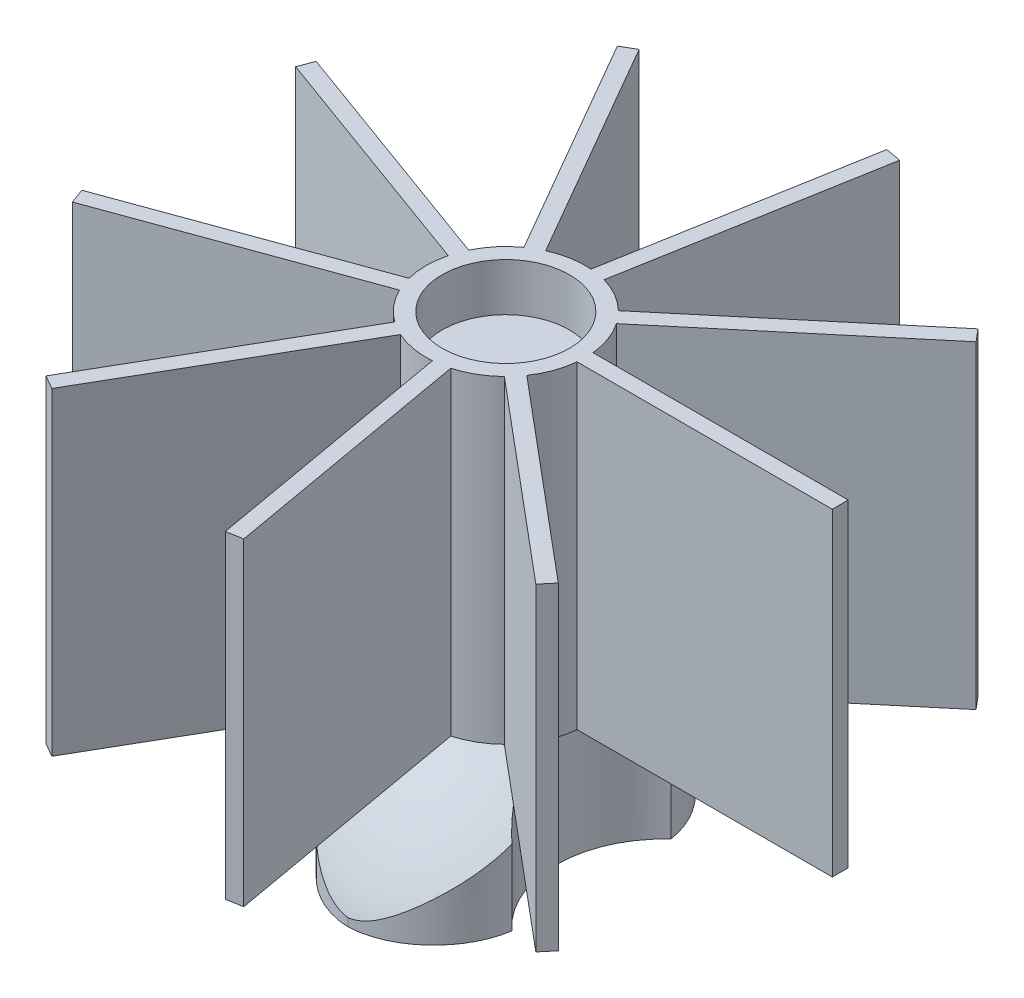
SolidWorks part; units mm, degrees
ref_plane "Front Plane" through (0, 0, 0) normal (0, 0, 1) x (1, 0, 0)
ref_plane "Top Plane" through (0, 0, 0) normal (0, 1, 0) x (1, 0, 0)
ref_plane "Right Plane" through (0, 0, 0) normal (1, 0, 0) x (0, 0, -1)
sketch "Sketch1" plane through (0, 0, 0) normal (0, 1, 0) x (1, 0, 0)
  circle A0 centre (0, 0) radius 5
  circle A1 centre (0, 0) radius 3
  dimension "D1" = 6
  dimension "D2" = 10
extrude "Boss-Extrude2" add sketch "Sketch1" along normal mid plane 35
sketch "Sketch4" plane through (0, 17.5, 0) normal (0, 1, 0) x (1, 0, 0)
  line L0 (3, 0) -> (21, 0)
  circle A0 centre (0, 0) radius 3 construction
  dimension "D1" = 18
extrude "Extrude-Thin1" add sketch "Sketch4" against normal blind 35 thin thin type mid plane wall 1
pattern_circular "CirPattern1" count 9 over 360 about axis through (0, 0, 0) along (0, 1, 0) of "Extrude-Thin1"
ref_plane "Plane1" through (0, -17.5, 0) normal (0, -1, 0) x (-1, 0, 0)
sketch "Sketch5" plane through (0, -17.5, 0) normal (0, -1, 0) x (-1, 0, 0)
  circle A0 centre (0, 0) radius 3
extrude "Boss-Extrude3" add sketch "Sketch5" against normal blind 15
sketch "Sketch6" plane through (0, -17.5, 0) normal (0, -1, 0) x (-1, 0, 0)
  circle A0 centre (0, 0) radius 3.5
  circle A1 centre (0, 0) radius 5
  circle A2 centre (0, 0) radius 1.5
  dimension "D1" = 1.5
  dimension "D2" = 10
  dimension "D3" = 2
extrude "Cut-Extrude1" cut sketch "Sketch6" against normal blind 6 contours A0 A2
sketch "Sketch15" plane through (0, -17.5, 0) normal (0, -1, 0) x (1, 0, 0)
  circle A0 centre (0, 0) radius 1.5
extrude "Cut-Extrude2" cut sketch "Sketch15" against normal blind 2
sketch "Sketch17" plane through (0, -17.5, 0) normal (0, -1, 0) x (1, 0, 0)
  line L0 (21, -0.5) -> (21, 0.5) construction
  circle A0 centre (18.5, 0) radius 2.5
  dimension "D1" = 5
  dimension "D2" = 2.5
extrude "Boss-Extrude4" add sketch "Sketch17" against normal blind 3
sketch "Sketch18" plane through (0, -17.5, 0) normal (0, -1, 0) x (1, 0, 0)
  circle A0 centre (18.5, 0) radius 2
  dimension "D1" = 4
extrude "Cut-Extrude3" cut sketch "Sketch18" against normal blind 2
sketch "Sketch19" plane through (0, 17.5, 0) normal (0, 1, 0) x (1, 0, 0)
  circle A0 centre (0, 0) radius 4
  circle A1 centre (0, 0) radius 3 construction
  dimension "D1" = 1
extrude "Cut-Extrude4" cut sketch "Sketch19" against normal up to surface (20 mm away) up to face at (0, -2.5, -3)
sketch "Sketch20" plane through (0, -17.5, 0) normal (0, -1, 0) x (-1, 0, 0)
  line L1 (22.8386, 22.8623) -> (-22.8386, 22.8623)
  line L2 (22.8386, 22.8623) -> (22.8386, -22.8623)
  line L3 (22.8386, -22.8623) -> (-22.8386, -22.8623)
  line L4 (-22.8386, 22.8623) -> (-22.8386, -22.8623)
  line L5 (22.8386, 22.8623) -> (-22.8386, -22.8623) construction
  line L6 (22.8386, -22.8623) -> (-22.8386, 22.8623) construction
  point P0 (0, 0)
extrude "Cut-Extrude5" cut sketch "Sketch20" against normal blind 8
sketch "Sketch21" plane through (0, -9.5, 0) normal (0, -1, 0) x (1, 0, 0)
  circle A0 centre (0, 0) radius 3
  dimension "D1" = 6
extrude "Boss-Extrude5" add sketch "Sketch21" along normal blind 1
sketch "Sketch22" plane through (0, 0, 0) normal (0, 0, 1) x (1, 0, 0)
  line L0 (0, 0) -> (0, -37.0893) construction
sketch "Sketch23" plane through (0, 0, 0) normal (1, 0, 0) x (0, 0, -1)
  line L0 (-8.7928, -17.5) -> (7.1377, -17.5) construction
  line L1 (-13.1155, -9.5) -> (-2.8148, -9.5) construction
  line L2 (-55, -17.5) -> (55, -17.5) construction
  line L3 (-3, -10.5) -> (-2, -10.5)
  line L4 (-3, -10.5) -> (3, -10.5) construction
  line L5 (-9.9121, -17.5) -> (-8.9121, -17.5)
  line L6 (0, -11.1307) -> (0, -16.3839) construction
  line L7 (0, 0) -> (0, -37.0893) construction
  line L8 (-8.9121, -17.5) -> (0, -17.5)
  line L9 (0, -17.5) -> (0, -10.5)
  line L10 (0, -10.5) -> (-2, -10.5)
  arc A0 (-3, -10.5) -> (-9.9121, -17.5) centre (0.7568, -21.1223) ccw
  dimension "D1" = 8
  dimension "D2" = 1
  dimension "D3" = 1
revolve "Revolve1" add sketch "Sketch23" angle 360 about L6
sketch "Sketch24" plane through (0, -17.5, 0) normal (0, -1, 0) x (1, 0, 0)
  circle A2 centre (0, 0) radius 9.9121
  circle A3 centre (0, 0) radius 9.9121
  dimension "D1" = 0
extrude "Boss-Extrude6" add sketch "Sketch24" along normal blind 0.5
sketch "Sketch25" plane through (0, -18, 0) normal (0, -1, 0) x (1, 0, 0)
  line L0 (-1.1163, 9.8491) -> (1.1163, -9.8491) construction
  circle A0 centre (0, 0) radius 9.9121 construction
  circle A1 centre (-0.5667, 5) radius 3.2
  point P6 (0, 0)
  dimension "D1" = 6.4
  dimension "D2" = 5
extrude "Cut-Extrude6" cut sketch "Sketch25" against normal blind 2.1
sketch "Sketch26" plane through (0, -18, 0) normal (0, -1, 0) x (1, 0, 0)
  circle A0 centre (-0.5667, 5) radius 3.2
extrude "Boss-Extrude7" add sketch "Sketch26" against normal blind 0.25
sketch "Sketch27" plane through (0, -18, 0) normal (0, -1, 0) x (1, 0, 0)
  line L0 (0, 9.9121) -> (0, -9.9121) construction
  line L1 (-9.9121, 0) -> (9.9121, 0) construction
  arc A1 (-7.6138, 6.3467) -> (-7.6138, -6.3467) centre (-9.9121, 0) cw
  circle A2 centre (0, 0) radius 9.9121 construction
  arc A3 (7.6138, 6.3467) -> (7.6138, -6.3467) centre (9.9121, 0) ccw
  arc A4 (7.6138, 6.3467) -> (7.6138, -6.3467) centre (0, 0) cw
  arc A5 (-7.6138, 6.3467) -> (-7.6138, -6.3467) centre (0, 0) ccw
  arc A6 (-7.6138, 6.3467) -> (0, 9.9121) centre (0, 0) cw
  arc A7 (7.6138, 6.3467) -> (0, 9.9121) centre (0, 0) ccw
  arc A8 (7.6138, -6.3467) -> (0, -9.9121) centre (0, 0) cw
  arc A9 (-7.6138, -6.3467) -> (0, -9.9121) centre (0, 0) ccw
  spline S0 degree 3 poles (-5.3686, 4.9919) (-4.9981, 7.5397) (-2.6164, 9.8379) (0, 9.9121) knots 0 0 0 0 1 1 1 1
  spline S1 degree 3 poles (5.3686, 4.9919) (4.9981, 7.5397) (2.6164, 9.8379) (0, 9.9121) knots 0 0 0 0 1 1 1 1
  spline S2 degree 3 poles (5.3686, -4.9919) (4.9981, -7.5397) (2.6164, -9.8379) (0, -9.9121) knots 0 0 0 0 1 1 1 1
  spline S3 degree 3 poles (-5.3686, -4.9919) (-4.9981, -7.5397) (-2.6164, -9.8379) (0, -9.9121) knots 0 0 0 0 1 1 1 1
  circle M1 centre (0, 0) radius 9.9121
extrude "Cut-Extrude8" cut sketch "Sketch27" against normal blind 7.5 contours A1 M1 | A3 M1 | S3 A1 M1 | A3 S2 M1 | A1 S0 M1 | S1 A3 M1
sketch "Sketch28" plane through (0, -18, 0) normal (0, -1, 0) x (1, 0, 0)
  circle A0 centre (0, 0) radius 0.5
  dimension "D1" = 1
extrude "Cut-Extrude9" cut sketch "Sketch28" against normal blind 1.5
sketch "Sketch29" plane through (0, 17.5, 0) normal (0, 1, 0) x (1, 0, 0)
  line L108 (3.4896, -3.5809) -> (15.7655, -13.8816)
  line L109 (15.7655, -13.8816) -> (16.4083, -13.1155)
  line L110 (16.4083, -13.1155) -> (4.1324, -2.8148)
  line L111 (4.9749, -0.5) -> (21, -0.5)
  line L112 (21, -0.5) -> (21, 0.5)
  line L113 (21, 0.5) -> (4.9749, 0.5)
  line L114 (4.1324, 2.8148) -> (16.4083, 13.1155)
  line L115 (16.4083, 13.1155) -> (15.7655, 13.8816)
  line L116 (15.7655, 13.8816) -> (3.4896, 3.5809)
  line L117 (1.3563, 4.8125) -> (4.139, 20.5941)
  line L118 (4.139, 20.5941) -> (3.1542, 20.7678)
  line L119 (3.1542, 20.7678) -> (0.3715, 4.9862)
  line L120 (-2.0545, 4.5584) -> (-10.067, 18.4365)
  line L121 (-10.067, 18.4365) -> (-10.933, 17.9365)
  line L122 (-10.933, 17.9365) -> (-2.9205, 4.0584)
  line L123 (-4.5039, 2.1714) -> (-19.5625, 7.6523)
  line L124 (-19.5625, 7.6523) -> (-19.9046, 6.7126)
  line L125 (-19.9046, 6.7126) -> (-4.8459, 1.2317)
  line L126 (-4.8459, -1.2317) -> (-19.9046, -6.7126)
  line L127 (-19.9046, -6.7126) -> (-19.5625, -7.6523)
  line L128 (-19.5625, -7.6523) -> (-4.5039, -2.1714)
  line L129 (-2.9205, -4.0584) -> (-10.933, -17.9365)
  line L130 (-10.933, -17.9365) -> (-10.067, -18.4365)
  line L131 (-10.067, -18.4365) -> (-2.0545, -4.5584)
  line L132 (0.3715, -4.9862) -> (3.1542, -20.7678)
  line L133 (3.1542, -20.7678) -> (4.139, -20.5941)
  line L134 (4.139, -20.5941) -> (1.3563, -4.8125)
  line L135 (3.4896, -3.5809) -> (15.7655, -13.8816)
  line L136 (15.7655, -13.8816) -> (16.4083, -13.1155)
  line L137 (16.4083, -13.1155) -> (4.1324, -2.8148)
  line L138 (4.9749, -0.5) -> (21, -0.5)
  line L139 (21, -0.5) -> (21, 0.5)
  line L140 (21, 0.5) -> (4.9749, 0.5)
  line L141 (4.1324, 2.8148) -> (16.4083, 13.1155)
  line L142 (16.4083, 13.1155) -> (15.7655, 13.8816)
  line L143 (15.7655, 13.8816) -> (3.4896, 3.5809)
  line L144 (1.3563, 4.8125) -> (4.139, 20.5941)
  line L145 (4.139, 20.5941) -> (3.1542, 20.7678)
  line L146 (3.1542, 20.7678) -> (0.3715, 4.9862)
  line L147 (-2.0545, 4.5584) -> (-10.067, 18.4365)
  line L148 (-10.067, 18.4365) -> (-10.933, 17.9365)
  line L149 (-10.933, 17.9365) -> (-2.9205, 4.0584)
  line L150 (-4.5039, 2.1714) -> (-19.5625, 7.6523)
  line L151 (-19.5625, 7.6523) -> (-19.9046, 6.7126)
  line L152 (-19.9046, 6.7126) -> (-4.8459, 1.2317)
  line L153 (-4.8459, -1.2317) -> (-19.9046, -6.7126)
  line L154 (-19.9046, -6.7126) -> (-19.5625, -7.6523)
  line L155 (-19.5625, -7.6523) -> (-4.5039, -2.1714)
  line L156 (-2.9205, -4.0584) -> (-10.933, -17.9365)
  line L157 (-10.933, -17.9365) -> (-10.067, -18.4365)
  line L158 (-10.067, -18.4365) -> (-2.0545, -4.5584)
  line L159 (0.3715, -4.9862) -> (3.1542, -20.7678)
  line L160 (3.1542, -20.7678) -> (4.139, -20.5941)
  line L161 (4.139, -20.5941) -> (1.3563, -4.8125)
  arc A36 (1.3563, -4.8125) -> (3.4896, -3.5809) centre (0, 0) ccw
  arc A37 (4.1324, -2.8148) -> (4.9749, -0.5) centre (0, 0) ccw
  arc A38 (4.9749, 0.5) -> (4.1324, 2.8148) centre (0, 0) ccw
  arc A39 (3.4896, 3.5809) -> (1.3563, 4.8125) centre (0, 0) ccw
  arc A40 (0.3715, 4.9862) -> (-2.0545, 4.5584) centre (0, 0) ccw
  arc A41 (-2.9205, 4.0584) -> (-4.5039, 2.1714) centre (0, 0) ccw
  arc A42 (-4.8459, 1.2317) -> (-4.8459, -1.2317) centre (0, 0) ccw
  arc A43 (-4.5039, -2.1714) -> (-2.9205, -4.0584) centre (0, 0) ccw
  arc A44 (-2.0545, -4.5584) -> (0.3715, -4.9862) centre (0, 0) ccw
  arc A45 (1.3563, -4.8125) -> (3.4896, -3.5809) centre (0, 0) ccw
  arc A46 (4.1324, -2.8148) -> (4.9749, -0.5) centre (0, 0) ccw
  arc A47 (4.9749, 0.5) -> (4.1324, 2.8148) centre (0, 0) ccw
  arc A48 (3.4896, 3.5809) -> (1.3563, 4.8125) centre (0, 0) ccw
  arc A49 (0.3715, 4.9862) -> (-2.0545, 4.5584) centre (0, 0) ccw
  arc A50 (-2.9205, 4.0584) -> (-4.5039, 2.1714) centre (0, 0) ccw
  arc A51 (-4.8459, 1.2317) -> (-4.8459, -1.2317) centre (0, 0) ccw
  arc A52 (-4.5039, -2.1714) -> (-2.9205, -4.0584) centre (0, 0) ccw
  arc A53 (-2.0545, -4.5584) -> (0.3715, -4.9862) centre (0, 0) ccw
  dimension "D1" = 0
extrude "Cut-Extrude10" cut sketch "Sketch29" against normal blind 7
sketch "Sketch30" plane through (0, -2.5, 0) normal (0, 1, 0) x (1, 0, 0)
  circle A1 centre (0, 0) radius 4
  circle A2 centre (0, 0) radius 4
  dimension "D1" = 0
extrude "Boss-Extrude8" add sketch "Sketch30" along normal blind 10
equation "\"NumFlaps\"=9"
equation "\"D1@CirPattern1\"=\"NumFlaps\""
equation "\"FlapHeight\"=35"
equation "\"D1@Extrude-Thin1\"=\"FlapHeight\""
equation "\"FanBaseHeight\"=35"
equation "\"D1@Boss-Extrude2\"=\"FanBaseHeight\""
equation "\"FanExtrude\"=6"
equation "\"D1@Sketch1\"=\"FanExtrude\""
equation "\"magnet_diameter\"= 6.4"
equation "\"magnet_length\"= 2.1"
equation "\"magnet_distance\"= 5"
equation "\"D1@Sketch25\"=\"magnet_diameter\""
equation "\"D2@Sketch25\"=\"magnet_distance\""
equation "\"D1@Cut-Extrude6\"=\"magnet_length\""
equation "\"CutglobeArc\"=6.75"
equation "\"FanExtraExtrude\"=7"
equation "\"D1@Cut-Extrude10\"=\"FanExtraExtrude\""
